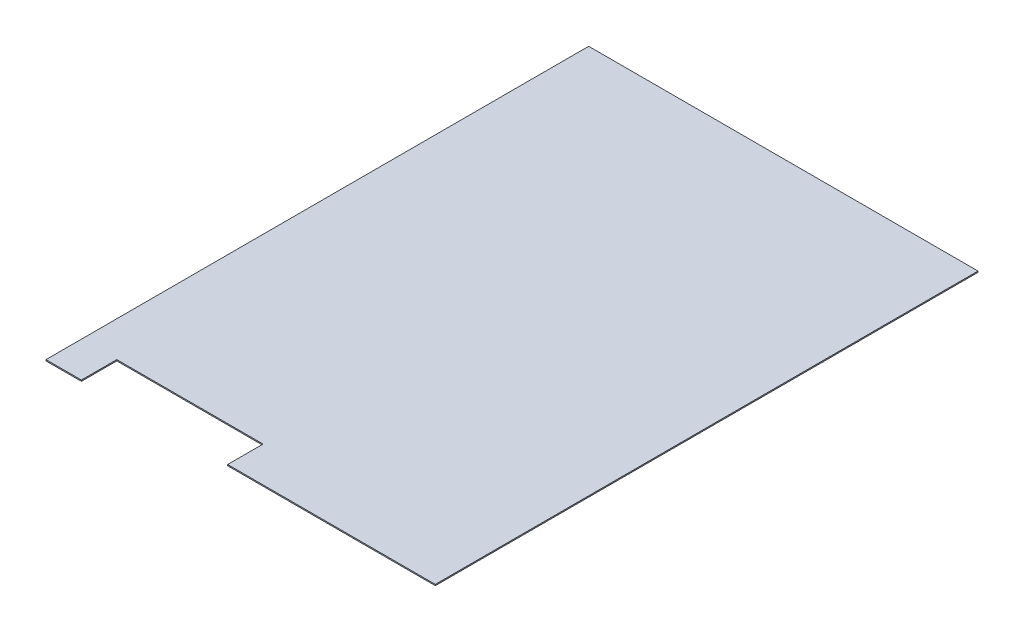
SolidWorks part; units mm, degrees
ref_plane "Front Plane" through (0, 0, 0) normal (0, 0, 1) x (1, 0, 0)
ref_plane "Top Plane" through (0, 0, 0) normal (0, 1, 0) x (1, 0, 0)
ref_plane "Right Plane" through (0, 0, 0) normal (1, 0, 0) x (0, 0, -1)
sketch "Sketch1" plane through (0, 0, 0) normal (0, 1, 0) x (1, 0, 0)
  line L1 (-82.5, 115) -> (82.5, 115)
  line L2 (-82.5, 115) -> (-82.5, -115)
  line L3 (-82.5, -115) -> (82.5, -115)
  line L4 (82.5, 115) -> (82.5, -115)
  line L5 (-82.5, 115) -> (82.5, -115) construction
  line L6 (-82.5, -115) -> (82.5, 115) construction
  point P0 (0, 0)
  dimension "D1" = 230
  dimension "D2" = 165
extrude "Boss-Extrude1" add sketch "Sketch1" along normal blind 0.5
sketch "Sketch2" plane through (0, 0.5, 0) normal (0, 1, 0) x (1, 0, 0)
  line L0 (-67.5, -115) -> (-67.5, -100)
  line L1 (-82.5, -115) -> (82.5, -115) construction
  line L2 (-67.5, -100) -> (-5.5, -100)
  line L3 (-5.5, -100) -> (-5.5, -115)
  line L4 (-5.5, -115) -> (-67.5, -115)
  line L5 (-82.5, 115) -> (-82.5, -115) construction
  dimension "D1" = 62
  dimension "D2" = 15
  dimension "D3" = 15
extrude "Cut-Extrude1" cut sketch "Sketch2" against normal blind 10
